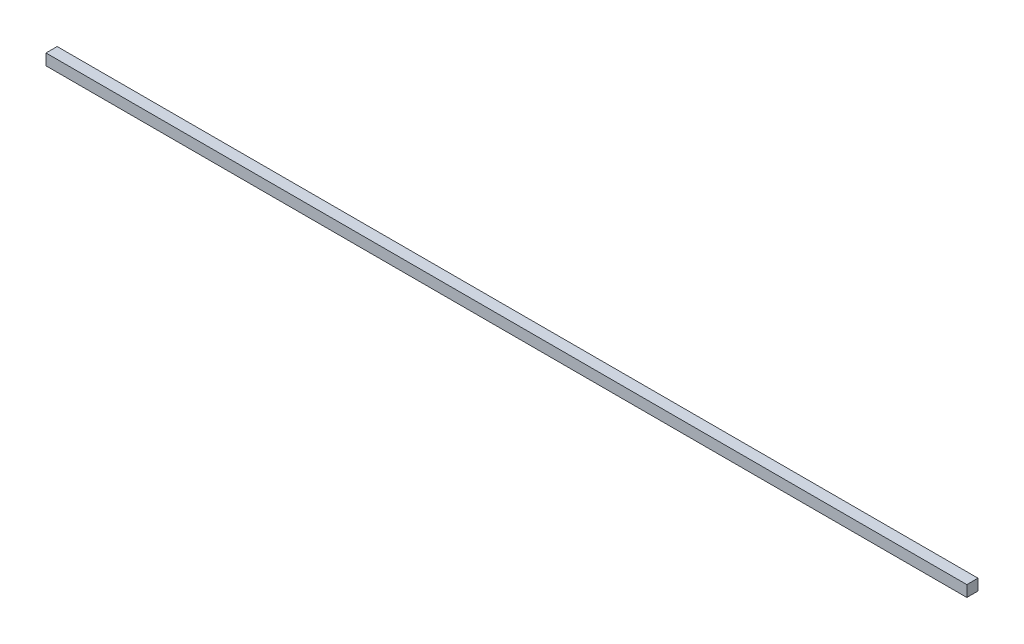
SolidWorks part; units mm, degrees
ref_plane "Front Plane" through (0, 0, 0) normal (0, 0, 1) x (1, 0, 0)
ref_plane "Top Plane" through (0, 0, 0) normal (0, 1, 0) x (1, 0, 0)
ref_plane "Right Plane" through (0, 0, 0) normal (1, 0, 0) x (0, 0, -1)
other "Configuration Table"
sketch "Sketch1" plane through (0, 0, 0) normal (0, 0, 1) x (1, 0, 0)
  line L1 (20, 1562) -> (680, 1562)
  line L2 (20, 1562) -> (20, 1570)
  line L3 (20, 1570) -> (680, 1570)
  line L4 (680, 1562) -> (680, 1570)
extrude "TOPPING_klape_kat1_pivot_mil_1" add sketch "Sketch1" along normal blind 8 from offset 22 separate body
